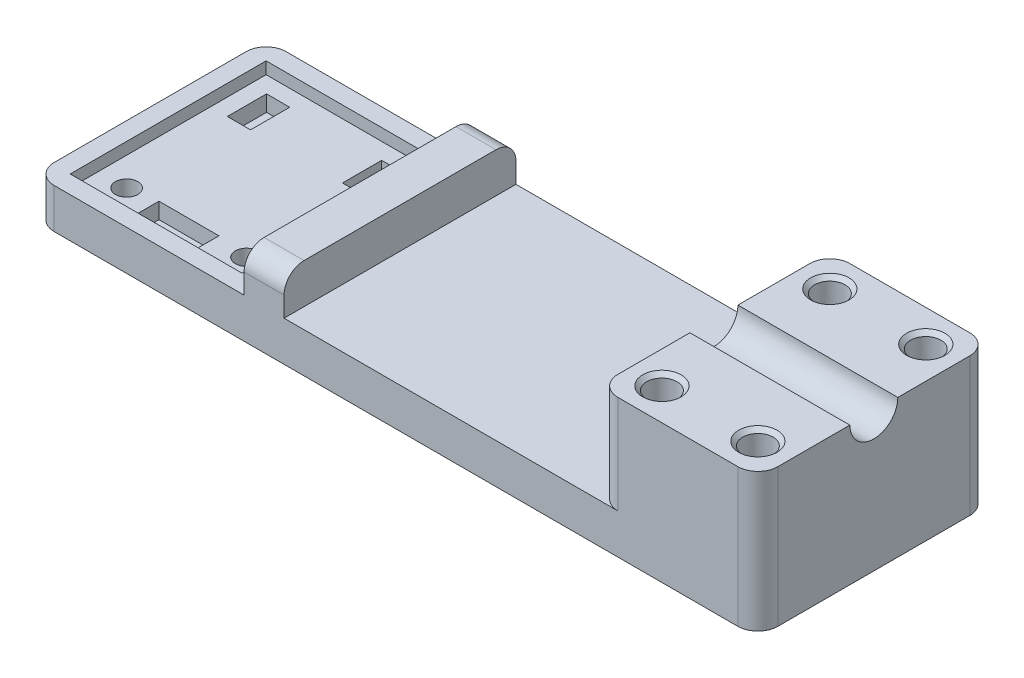
SolidWorks part; units mm, degrees
material "PET"
ref_plane "Přední rovina" through (0, 0, 0) normal (0, 0, 1) x (1, 0, 0)
ref_plane "Horní rovina" through (0, 0, 0) normal (0, 1, 0) x (1, 0, 0)
ref_plane "Pravá rovina" through (0, 0, 0) normal (1, 0, 0) x (0, 0, -1)
sketch "Skica1" plane through (0, 0, 0) normal (0, 0, 1) x (1, 0, 0)
  line L0 (0, 0) -> (90.5, 0)
  line L1 (90.5, 0) -> (90.5, 17.3)
  line L2 (90.5, 17.3) -> (70.5, 17.3)
  line L4 (70.5, 5) -> (0, 5)
  line L5 (0, 5) -> (0, 0)
  line L6 (70.5, 17.3) -> (70.5, 5)
  dimension "D1" = 5
  dimension "D2" = 17.3
  dimension "D3" = 20
  dimension "D5" = 90.5
extrude "Přidat vysunutím1" add sketch "Skica1" along normal blind 29
sketch "Skica2" plane through (0, 5, 0) normal (0, 1, 0) x (1, 0, 0)
  line L0 (0, -29) -> (0, 0) construction
  line L1 (23.75, -26.75) -> (2.25, -26.75)
  line L6 (23.75, -26.75) -> (23.75, -2.25)
  line L7 (23.75, -2.25) -> (2.25, -2.25)
  line L8 (2.25, -26.75) -> (2.25, -2.25)
  line L9 (23.75, -26.75) -> (2.25, -2.25) construction
  line L10 (23.75, -2.25) -> (2.25, -26.75) construction
  line L11 (0, -14.5) -> (70.5, -14.5) construction
  line L13 (70.5, -29) -> (70.5, 0) construction
  point P0 (13, -14.5)
  dimension "D1" = 24.5
  dimension "D2" = 21.5
  dimension "D3" = 2.25
extrude "Odebrat vysunutím1" cut sketch "Skica2" against normal blind 1.5
sketch "Skica3" plane through (0, 3.5, 0) normal (0, 1, 0) x (1, 0, 0)
  line L0 (2.25, -14.5) -> (23.75, -14.5) construction
  line L1 (2.25, -2.25) -> (2.25, -26.75) construction
  line L2 (23.75, -26.75) -> (23.75, -2.25) construction
  line L4 (23.1, -26.15) -> (2.9, -26.15) construction
  line L5 (23.1, -26.15) -> (23.1, -2.85) construction
  line L6 (23.1, -2.85) -> (2.9, -2.85) construction
  line L7 (2.9, -26.15) -> (2.9, -2.85) construction
  line L8 (23.1, -26.15) -> (2.9, -2.85) construction
  line L9 (23.1, -2.85) -> (2.9, -26.15) construction
  circle A0 centre (20.8, -23.25) radius 1.4
  circle A1 centre (5.8, -23.25) radius 1.4
  point P6 (13, -14.5)
  point P15 (5.55, -23.4)
  dimension "D3" = 2.8
  dimension "D6" = 2.8
  dimension "D5" = 15
  dimension "D8" = 1.5
  dimension "D1" = 23.3
  dimension "D2" = 20.2
  dimension "D4" = 1.5
extrude "Odebrat vysunutím2" cut sketch "Skica3" against normal up to surface (3.5 mm away) up to face at (45.25, 0, 14.5)
sketch "Skica6" plane through (0, 3.5, 0) normal (0, 1, 0) x (1, 0, 0)
  line L0 (2.25, -14.5) -> (23.75, -14.5) construction
  line L1 (2.25, -2.25) -> (2.25, -26.75) construction
  line L2 (23.75, -26.75) -> (23.75, -2.25) construction
  line L3 (13, -2.95) -> (13, -26.05) construction
  line L4 (2.9, -26.05) -> (23.1, -26.05) construction
  line L5 (2.9, -26.05) -> (2.9, -2.95) construction
  line L6 (2.9, -2.95) -> (23.1, -2.95) construction
  line L7 (23.1, -26.05) -> (23.1, -2.95) construction
  line L8 (2.9, -26.05) -> (23.1, -2.95) construction
  line L9 (2.9, -2.95) -> (23.1, -26.05) construction
  line L10 (4.35, -4.3) -> (7.25, -4.3)
  line L11 (4.35, -4.3) -> (4.35, -9.2)
  line L12 (4.35, -9.2) -> (7.25, -9.2)
  line L13 (7.25, -4.3) -> (7.25, -9.2)
  line L14 (4.35, -4.3) -> (7.25, -9.2) construction
  line L15 (4.35, -9.2) -> (7.25, -4.3) construction
  line L16 (21.65, -9.2) -> (18.75, -9.2)
  line L17 (18.75, -4.3) -> (18.75, -9.2)
  line L18 (21.65, -4.3) -> (18.75, -4.3)
  line L19 (21.65, -4.3) -> (21.65, -9.2)
  line L21 (9.25, -22.65) -> (16.75, -22.65)
  line L22 (9.25, -22.65) -> (9.25, -25.55)
  line L23 (9.25, -25.55) -> (16.75, -25.55)
  line L24 (16.75, -22.65) -> (16.75, -25.55)
  line L25 (9.25, -22.65) -> (16.75, -25.55) construction
  line L26 (9.25, -25.55) -> (16.75, -22.65) construction
  point P6 (13, -14.5)
  point P15 (5.8, -6.75)
  point P26 (13, -24.1)
  dimension "D1" = 23.1
  dimension "D2" = 20.2
  dimension "D3" = 1.35
  dimension "D4" = 1.45
  dimension "D5" = 2.9
  dimension "D6" = 4.9
  dimension "D7" = 7.5
  dimension "D8" = 0.5
  dimension "D9" = 2.9
extrude "Odebrat vysunutím5" cut sketch "Skica6" against normal blind 2
fillet "Zaoblit1" radius 2.5 2 edges at (0, 2.5, 0) (0, 2.5, 29)
fillet "Zaoblit2" radius 2.5 4 edges at (70.5, 11.15, 0) (70.5, 11.15, 29) (90.5, 8.65, 0) (90.5, 8.65, 29)
sketch "Skica10" plane through (0, 17.3, 0) normal (0, 1, 0) x (1, 0, 0)
  line L0 (70.5, -14.5) -> (90.5, -14.5) construction
  line L1 (70.5, -26.5) -> (70.5, -2.5) construction
  line L2 (90.5, -26.5) -> (90.5, -2.5) construction
  line L3 (70.5, -26.5) -> (70.5, -2.5) construction
  line L4 (86.5, -25) -> (74.5, -25) construction
  line L5 (86.5, -25) -> (86.5, -4) construction
  line L6 (86.5, -4) -> (74.5, -4) construction
  line L7 (74.5, -25) -> (74.5, -4) construction
  line L8 (86.5, -25) -> (74.5, -4) construction
  line L9 (86.5, -4) -> (74.5, -25) construction
  line L10 (88, 0) -> (73, 0) construction
  circle A0 centre (74.5, -4) radius 1.9
  circle A1 centre (86.5, -4) radius 1.9
  circle A2 centre (86.5, -25) radius 1.9
  circle A3 centre (74.5, -25) radius 1.9
  point P6 (80.5, -14.5)
  dimension "D1" = 3.8
  dimension "D2" = 3.8
  dimension "D3" = 4
  dimension "D4" = 4
extrude "Odebrat vysunutím7" cut sketch "Skica10" against normal up to surface (17.3 mm away) up to face at (20.8, 0, 24.65)
sketch "Skica20" plane through (90.5, 0, 0) normal (1, 0, 0) x (0, 0, -1)
  line L0 (-26.5, 17.3) -> (-2.5, 17.3) construction
  circle A0 centre (-14.5, 17.3) radius 3
  dimension "D1" = 6
extrude "Odebrat vysunutím8" cut sketch "Skica20" against normal up to surface (20 mm away) up to face at (70.5, 11.15, 14.5)
chamfer "Zkosení1" distance 0.5 angle 45 4 edges at (88.4, 17.3, 25) (76.4, 17.3, 25) (84.6, 17.3, 4) (72.6, 17.3, 4)
sketch "Skica21" plane through (0, 5, 0) normal (0, 1, 0) x (1, 0, 0)
  line L0 (73, 0) -> (2.5, 0) construction
  line L1 (26.2455, 0) -> (31.2455, 0)
  line L2 (26.2455, 0) -> (26.2455, -29)
  line L3 (26.2455, -29) -> (31.2455, -29)
  line L4 (31.2455, 0) -> (31.2455, -29)
  line L5 (26.2455, 0) -> (31.2455, -29) construction
  line L6 (26.2455, -29) -> (31.2455, 0) construction
  line L7 (73, -29) -> (2.5, -29) construction
  line L8 (23.75, -26.75) -> (23.75, -2.25) construction
  point P4 (28.7455, -14.5)
  dimension "D1" = 2.4955
  dimension "D2" = 5
extrude "Přidat vysunutím2" add sketch "Skica21" along normal blind 5
fillet "Zaoblit4" radius 2.5 2 edges at (28.7455, 10, 0) (28.7455, 10, 29)
